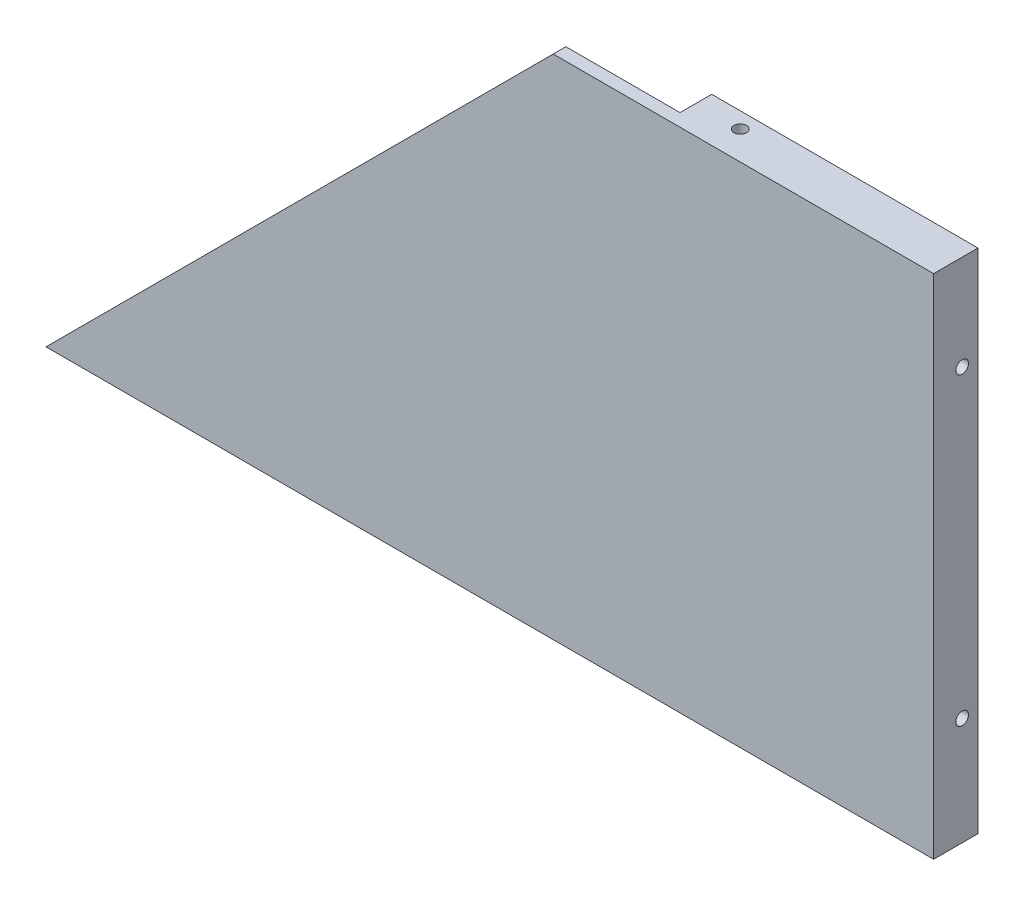
SolidWorks part; units mm, degrees
ref_plane "前视基准面" through (0, 0, 0) normal (0, 0, 1) x (1, 0, 0)
ref_plane "上视基准面" through (0, 0, 0) normal (0, 1, 0) x (1, 0, 0)
ref_plane "右视基准面" through (0, 0, 0) normal (1, 0, 0) x (0, 0, -1)
sketch "草图1" plane through (0, 0, 0) normal (0, 0, 1) x (1, 0, 0)
  line L0 (0, 0) -> (-280, 0)
  line L1 (-280, 0) -> (-120, 160)
  line L2 (-120, 160) -> (0, 160)
  line L3 (0, 160) -> (0, 0)
  dimension "D1" = 280
  dimension "D2" = 160
  dimension "D3" = 45
extrude "凸台-拉伸1" add sketch "草图1" along normal blind 4
sketch "草图3" plane through (0, 0, 0) normal (0, -1, 0) x (1, 0, 0)
  line L0 (-280, 0) -> (0, 0) construction
  line L1 (-260, 0) -> (0, 0)
  line L2 (-260, 0) -> (-260, -10)
  line L3 (-260, -10) -> (0, -10)
  line L4 (0, 0) -> (0, -10)
  line L5 (-210, -5) -> (-73.7197, -5) construction
  line L6 (-140, -5) -> (-3.7197, -5) construction
  line L7 (-70, -5) -> (66.2803, -5) construction
  line L8 (-210, -5) -> (-140, -5) construction
  circle A0 centre (-210, -5) radius 2
  circle A1 centre (-140, -5) radius 2
  circle A2 centre (-70, -5) radius 2
  dimension "D2" = 4
  dimension "D1" = 20
  dimension "D3" = 10
  dimension "D4" = 50
  dimension "D5" = 3
  dimension "D6" = 70
extrude "凸台-拉伸2" add sketch "草图3" against normal blind 4
sketch "草图4" plane through (0, 0, 0) normal (1, 0, 0) x (0, 0, -1)
  line L0 (5, 123.5026) -> (5, -8.7878) construction
  line L1 (0, 160) -> (10, 160)
  line L2 (0, 160) -> (0, 4)
  line L3 (0, 4) -> (10, 4)
  line L4 (10, 160) -> (10, 4)
  circle A0 centre (5, 34) radius 2
  circle A1 centre (5, 130) radius 2
  dimension "D1" = 4
  dimension "D2" = 4
  dimension "D3" = 30
  dimension "D4" = 30
extrude "凸台-拉伸3" add sketch "草图4" against normal blind 4
sketch "草图5" plane through (0, 160, 0) normal (0, 1, 0) x (1, 0, 0)
  line L0 (-4, 0) -> (-120, 0) construction
  line L1 (-84, 0) -> (-4, 0)
  line L2 (-84, 0) -> (-84, 10)
  line L3 (-84, 10) -> (-4, 10)
  line L4 (-4, 0) -> (-4, 10)
  line L5 (-260, 10) -> (-4, 10) construction
  line L6 (-4, 10) -> (-4, 0) construction
  circle A0 centre (-70, 5) radius 2
  dimension "D2" = 4
  dimension "D1" = 80
extrude "凸台-拉伸4" add sketch "草图5" against normal blind 4
sketch "草图7" plane through (-140, 140, 0) normal (-0.7071, 0.7071, 0) x (0, 0, 1)
  line L0 (0, 28.2843) -> (0, -197.9899) construction
  line L1 (0, 8.2843) -> (-10, 8.2843)
  line L2 (0, 8.2843) -> (0, -157.9899)
  line L3 (0, -157.9899) -> (-10, -157.9899)
  line L4 (-10, 8.2843) -> (-10, -157.9899)
  line L5 (-10, -181.0193) -> (-10, 0) construction
  line L7 (4, 28.2843) -> (0, 28.2843) construction
  line L8 (4, -197.9899) -> (0, -197.9899) construction
  circle A0 centre (-5, -11.7157) radius 2
  circle A1 centre (-5, -137.9899) radius 2
  point P12 (2, 28.2843)
  point P13 (2, -197.9899)
  dimension "D3" = 4
  dimension "D4" = 4
  dimension "D1" = 20
  dimension "D2" = 40
  dimension "D5" = 20
  dimension "D6" = 20
  dimension "D7" = 5
extrude "凸台-拉伸5" add sketch "草图7" against normal blind 4
